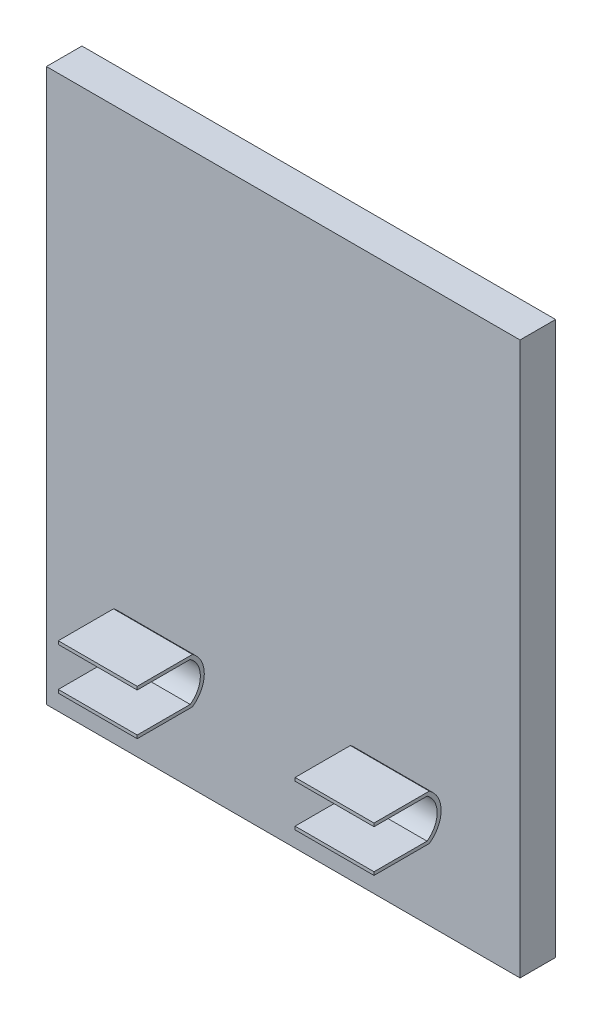
SolidWorks part; units mm, degrees
ref_plane "Front Plane" through (0, 0, 0) normal (0, 0, 1) x (1, 0, 0)
ref_plane "Top Plane" through (0, 0, 0) normal (0, 1, 0) x (1, 0, 0)
ref_plane "Right Plane" through (0, 0, 0) normal (1, 0, 0) x (0, 0, -1)
sketch "Sketch1" plane through (0, 0, 0) normal (0, 0, 1) x (1, 0, 0)
  line L1 (0, 0) -> (120, 0)
  line L2 (0, 0) -> (0, 140)
  line L3 (0, 140) -> (120, 140)
  line L4 (120, 0) -> (120, 140)
  dimension "D1" = 140
  dimension "D2" = 120
extrude "Boss-Extrude1" add sketch "Sketch1" along normal blind 9
sketch "Sketch3" plane through (120, 0, 0) normal (1, 0, 0) x (0, 0, -1)
  line L0 (-4.5, 0) -> (-4.5, 21) construction
  line L1 (-9, 0) -> (0, 0) construction
  line L3 (-9, 21) -> (0, 21)
  line L4 (-9, 21) -> (-9, 0)
  line L5 (-9, 0) -> (0, 0)
  line L6 (0, 21) -> (0, 0)
  line L7 (-9, 21) -> (0, 0) construction
  line L8 (-9, 0) -> (0, 21) construction
  line L17 (-12.5724, 21.82) -> (-26, 21.82)
  line L19 (-26, 31.685) -> (-12.5724, 31.685)
  line L20 (-26, 32.505) -> (-26, 31.685)
  line L21 (-26, 21.82) -> (-26, 21)
  line L22 (-12, 21) -> (-26, 21)
  line L23 (-12, 32.505) -> (-26, 32.505)
  arc A0 (-12, 21) -> (-12, 32.505) centre (-16.0152, 26.7525) ccw
  arc A1 (-12.5724, 21.82) -> (-12.5724, 31.685) centre (-16.0152, 26.7525) ccw
  point P4 (-4.5, 10.5)
  dimension "D4" = 1
  dimension "D1" = 21
extrude "Boss-Extrude2" add sketch "Sketch3" against normal blind 120
sketch "Sketch4" plane through (120, 0, 0) normal (1, 0, 0) x (0, 0, -1)
  line L0 (-9, 0) -> (-9, 140) construction
  line L1 (-9, 32.505) -> (-26, 32.505)
  line L2 (-9, 32.505) -> (-9, 21)
  line L3 (-9, 21) -> (-26, 21)
  line L4 (-26, 32.505) -> (-26, 21)
extrude "Cut-Extrude1" cut sketch "Sketch4" against normal blind 20
sketch "Sketch5" plane through (0, 0, 0) normal (-1, 0, 0) x (0, 0, 1)
  line L0 (9, 140) -> (9, 0) construction
  line L1 (9, 32.7033) -> (26, 32.7033)
  line L2 (9, 32.7033) -> (9, 21)
  line L3 (9, 21) -> (26, 21)
  line L4 (26, 32.7033) -> (26, 21)
extrude "Cut-Extrude2" cut sketch "Sketch5" against normal blind 20
sketch "Sketch6" plane through (0, 0, 0) normal (0, -1, 0) x (1, 0, 0)
  line L0 (20, 19) -> (100, 19) construction
  line L1 (20, 12) -> (20, 26) construction
  line L2 (100, 26) -> (100, 12) construction
  line L3 (0, 9) -> (120, 9) construction
  line L4 (20, 26) -> (40, 26)
  line L5 (20, 26) -> (20, 9)
  line L6 (20, 9) -> (40, 9)
  line L7 (40, 26) -> (40, 9)
  line L9 (100, 26) -> (80, 26)
  line L10 (100, 26) -> (100, 9)
  line L11 (100, 9) -> (80, 9)
  line L12 (80, 26) -> (80, 9)
  line L13 (40, 26) -> (80, 26)
  line L14 (40, 26) -> (40, 9)
  line L15 (40, 9) -> (80, 9)
  line L16 (80, 26) -> (80, 9)
  line M9 (120, 9) -> (0, 9)
  dimension "D1" = 20
  dimension "D2" = 20
extrude "Cut-Extrude3" cut sketch "Sketch6" against normal blind 80 contours L7 L0 L12 L13 | L0 L14 L16 M9
sketch "Sketch12" plane through (0, 0, 0) normal (0, 0, -1) x (-1, 0, 0)
  text T0 "F G P" font "@Adobe Gothic Std B" height in points 72
extrude "Boss-Extrude3" add sketch "Sketch12" along normal blind 1.15
